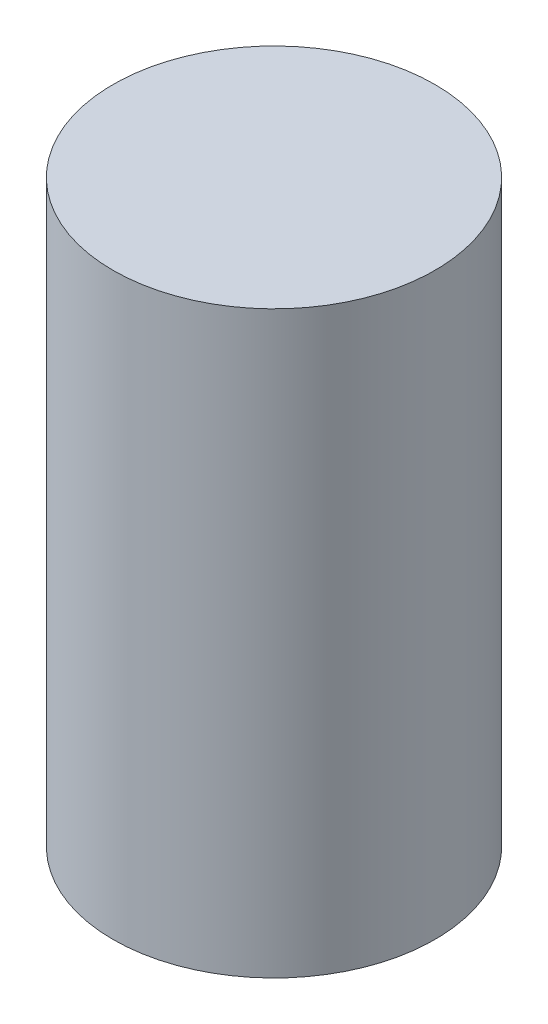
SolidWorks part; units mm, degrees
ref_plane "前视基准面" through (0, 0, 0) normal (0, 0, 1) x (1, 0, 0)
ref_plane "上视基准面" through (0, 0, 0) normal (0, 1, 0) x (1, 0, 0)
ref_plane "右视基准面" through (0, 0, 0) normal (1, 0, 0) x (0, 0, -1)
sketch "草图1" plane through (0, 0, 0) normal (0, 1, 0) x (1, 0, 0)
  circle A0 centre (-33.6117, 0) radius 10
extrude "凸台-拉伸1" add sketch "草图1" along normal blind 36
